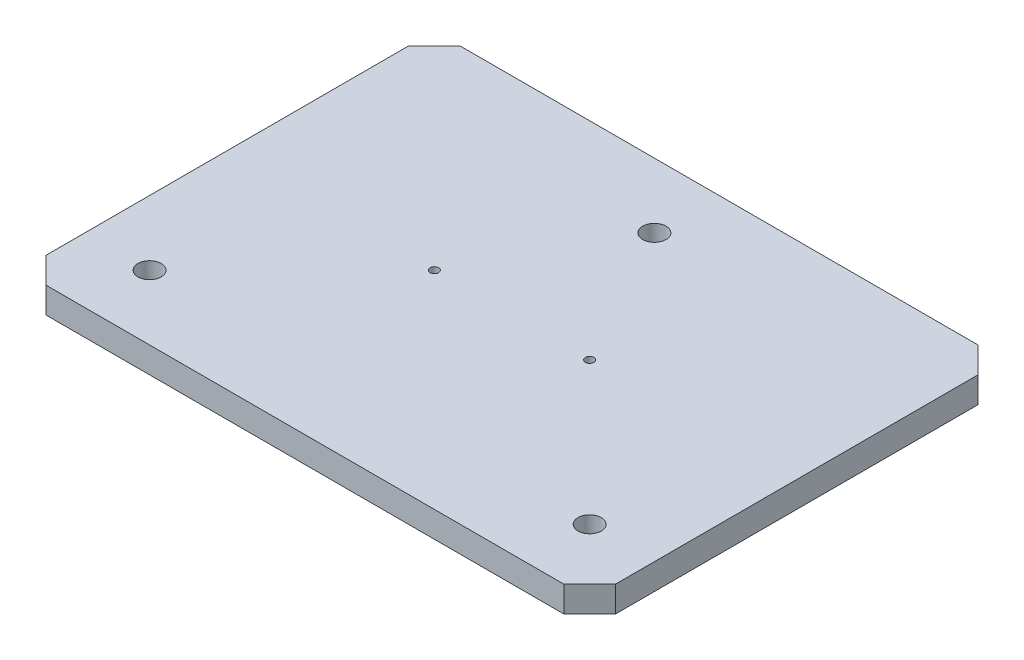
SolidWorks part; units mm, degrees
ref_plane "Front Plane" through (0, 0, 0) normal (0, 0, 1) x (1, 0, 0)
ref_plane "Top Plane" through (0, 0, 0) normal (0, 1, 0) x (1, 0, 0)
ref_plane "Right Plane" through (0, 0, 0) normal (1, 0, 0) x (0, 0, -1)
sketch "Sketch1" plane through (0, 0, 0) normal (0, 1, 0) x (1, 0, 0)
  line L1 (110, -80) -> (-110, -80)
  line L2 (110, -80) -> (110, 80)
  line L3 (110, 80) -> (-110, 80)
  line L4 (-110, -80) -> (-110, 80)
  line L5 (110, -80) -> (-110, 80) construction
  line L6 (110, 80) -> (-110, -80) construction
  point P0 (0, 0)
  dimension "D1" = 220
  dimension "D2" = 160
extrude "Boss-Extrude1" add sketch "Sketch1" along normal blind 10
chamfer "Chamfer1" distance 10 angle 45 4 edges at (-110, 5, -80) (110, 5, -80) (110, 5, 80) (-110, 5, 80)
sketch "Sketch2" plane through (0, 10, 0) normal (0, 1, 0) x (1, 0, 0)
  point P0 (-85, -55)
  point P1 (85, -55)
  point P2 (0, 55)
  point P3 (0, 0)
  point P5 (0, 0)
  dimension "D1" = 55
  dimension "D2" = 85
  dimension "D3" = 55
  dimension "D4" = 85
hole_wizard "M10x1.0 Tapped Hole1" positions "3DSketch1" profile "Sketch3" tap size "M10x1.0" standard "BSI" end condition through all
sketch3d "3DSketch1"
  point P0 (0, 10, -55)
  point P3 (-85, 10, 55)
  point P6 (85, 10, 55)
sketch "Sketch3" plane through (0, 10, -55) normal (1, 0, 0) x (0, 0, 1)
  line L0 (0, 0) -> (0, 10)
  line L1 (0, 10) -> (4.5, 10)
  line L2 (4.5, 10) -> (4.5, 0)
  line L5 (4.5, 0) -> (0, 0)
  line L11 (0, -6.35) -> (0, 107.95) construction
  dimension "Thru Tap Drill Dia." = 9
  dimension "Thru Tap Drill Depth" = 10
cosmetic thread "Hole Thread1"
cosmetic thread "Hole Thread2"
cosmetic thread "Hole Thread3"
sketch "Sketch4" plane through (0, 10, 0) normal (0, 1, 0) x (1, 0, 0)
  line L0 (0, 0) -> (30, 0) construction
  point P4 (30, 0)
  dimension "D1" = 30
hole_wizard "M4x0.7 Tapped Hole1" positions "3DSketch2" profile "Sketch5" tap size "M4x0.7" standard "BSI" end condition through all
sketch3d "3DSketch2"
  point P0 (30, 10, 0)
sketch "Sketch5" plane through (30, 10, 0) normal (1, 0, 0) x (0, 0, 1)
  line L0 (0, 0) -> (0, 10)
  line L1 (0, 10) -> (1.65, 10)
  line L2 (1.65, 10) -> (1.65, 0)
  line L5 (1.65, 0) -> (0, 0)
  line L11 (0, -6.35) -> (0, 107.95) construction
  dimension "Thru Tap Drill Dia." = 3.3
  dimension "Thru Tap Drill Depth" = 10
cosmetic thread "Hole Thread4"
mirror "Mirror1" about plane through (0, 0, 0) normal (1, 0, 0) of "M4x0.7 Tapped Hole1"
cosmetic thread "Hole Thread5"
equation "\"D4@Sketch2\"=\"D2@Sketch2\""
